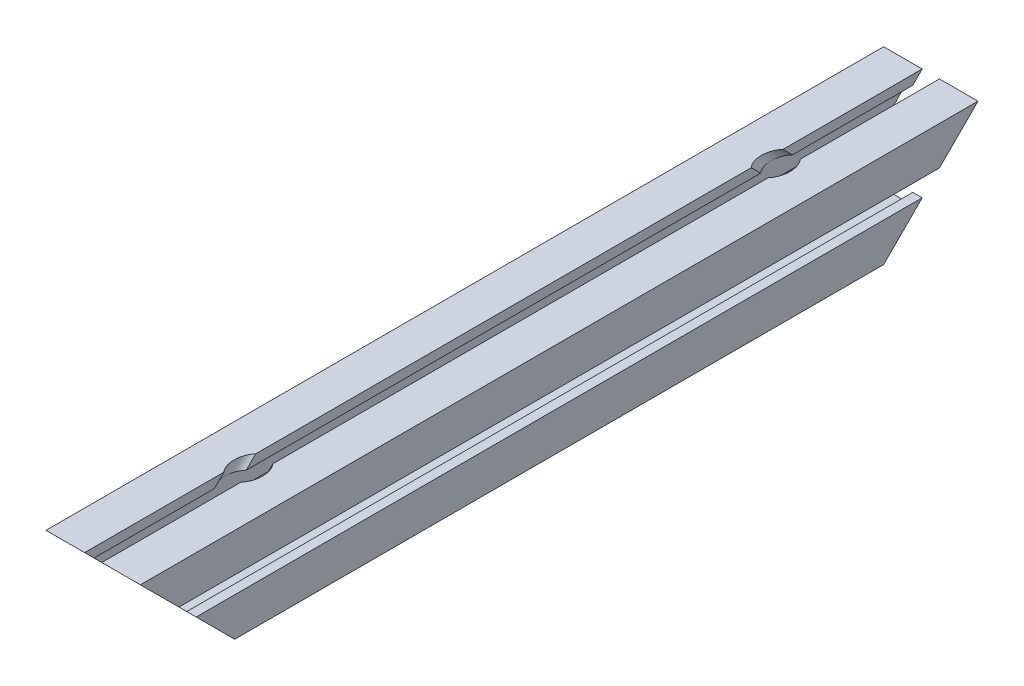
SolidWorks part; units mm, degrees
material "6061 Alloy"
ref_plane "Front Plane" through (0, 0, 0) normal (0, 0, 1) x (1, 0, 0)
ref_plane "Top Plane" through (0, 0, 0) normal (0, 1, 0) x (1, 0, 0)
ref_plane "Right Plane" through (0, 0, 0) normal (1, 0, 0) x (0, 0, -1)
sketch "Sketch1" plane through (0, 0, 0) normal (0, 0, 1) x (1, 0, 0)
  line L88 (-18, -4.1) -> (-22.5, -4.1)
  line L89 (-22.5, -4.1) -> (-22.5, -22.5)
  line L90 (-22.5, -22.5) -> (-4.1, -22.5)
  line L91 (-4.1, -22.5) -> (-4.1, -18)
  line L92 (-4.1, -18) -> (-6.8, -18)
  line L93 (-6.8, -18) -> (-6.8, -9.5)
  line L94 (-6.8, -9.5) -> (-4.5, -7.2)
  line L95 (-4.5, -7.2) -> (4.5, -7.2)
  line L96 (4.5, -7.2) -> (6.8, -9.5)
  line L97 (6.8, -9.5) -> (6.8, -18)
  line L98 (6.8, -18) -> (4.1, -18)
  line L99 (4.1, -18) -> (4.1, -22.5)
  line L100 (4.1, -22.5) -> (22.5, -22.5)
  line L101 (22.5, -22.5) -> (22.5, -4.1)
  line L102 (22.5, -4.1) -> (18, -4.1)
  line L103 (18, -4.1) -> (18, -6.8)
  line L104 (18, -6.8) -> (9.5, -6.8)
  line L105 (9.5, -6.8) -> (7.2, -4.5)
  line L106 (7.2, -4.5) -> (7.2, 4.5)
  line L107 (7.2, 4.5) -> (9.5, 6.8)
  line L108 (9.5, 6.8) -> (18, 6.8)
  line L109 (18, 6.8) -> (18, 4.1)
  line L110 (18, 4.1) -> (22.5, 4.1)
  line L111 (22.5, 4.1) -> (22.5, 22.5)
  line L112 (22.5, 22.5) -> (4.1, 22.5)
  line L113 (4.1, 22.5) -> (4.1, 18)
  line L114 (4.1, 18) -> (6.8, 18)
  line L115 (6.8, 18) -> (6.8, 9.5)
  line L116 (6.8, 9.5) -> (4.5, 7.2)
  line L117 (4.5, 7.2) -> (-4.5, 7.2)
  line L118 (-4.5, 7.2) -> (-6.8, 9.5)
  line L119 (-6.8, 9.5) -> (-6.8, 18)
  line L120 (-6.8, 18) -> (-4.1, 18)
  line L121 (-4.1, 18) -> (-4.1, 22.5)
  line L122 (-4.1, 22.5) -> (-22.5, 22.5)
  line L123 (-22.5, 22.5) -> (-22.5, 4.1)
  line L124 (-22.5, 4.1) -> (-18, 4.1)
  line L125 (-18, 4.1) -> (-18, 6.8)
  line L126 (-18, 6.8) -> (-9.5, 6.8)
  line L127 (-9.5, 6.8) -> (-7.2, 4.5)
  line L128 (-7.2, 4.5) -> (-7.2, -4.5)
  line L129 (-7.2, -4.5) -> (-9.5, -6.8)
  line L130 (-9.5, -6.8) -> (-18, -6.8)
  line L131 (-18, -6.8) -> (-18, -4.1)
  circle A5 centre (14.65, -14.65) radius 6
  circle A6 centre (-14.65, -14.65) radius 6
  circle A7 centre (0, 0) radius 3.75
  circle A8 centre (14.65, 14.65) radius 6
  circle A9 centre (-14.65, 14.65) radius 6
extrude "Extrude1" add sketch "Sketch1" along normal blind 199.7577 and the other way blind 199.7577
sketch "Sketch2" plane through (22.5, 0, 0) normal (1, 0, 0) x (0, 0, -1)
  line L0 (-199.7577, 4.1) -> (-199.7577, 22.5) construction
  line L1 (-199.7577, 4.1) -> (-199.7577, 22.5)
  line L2 (199.7577, -22.5) -> (-199.7577, -22.5) construction
  line L3 (199.7577, -22.5) -> (-199.7577, -22.5)
  line L4 (-199.7577, 22.5) -> (-154.7577, -22.5)
  line L5 (-154.7577, -22.5) -> (-199.7577, -22.5)
  line L6 (-199.7577, -22.5) -> (-199.7577, 22.5)
  line L7 (199.7577, 22.5) -> (199.7577, -22.5)
  line L8 (199.7577, -22.5) -> (154.7577, -22.5)
  line L9 (154.7577, -22.5) -> (199.7577, 22.5)
  line M2 (-199.7577, 22.5) -> (-199.7577, 4.1)
  line M3 (-199.7577, 4.1) -> (199.7577, 4.1)
  line M4 (199.7577, 4.1) -> (199.7577, 22.5)
  dimension "D1" = 45
  dimension "D2" = 45
extrude "Extrude2" cut sketch "Sketch2" against normal through all contours L6 L3 L4 M3 | L4 M2 M3 | L9 L3 L7 M3 | L9 M3 M4
ref_plane "Plane1" through (0, -73.3624, 73.3624) normal (0, -0.7071, 0.7071) x (1, 0, 0)
sketch "Sketch3" plane through (0, -88.6288, 88.6288) normal (0, -0.7071, 0.7071) x (1, 0, 0)
  line L0 (22.5, 157.1599) -> (22.5, 131.1384) construction
  line L1 (22.5, 157.1599) -> (4.1, 157.1599) construction
  circle A0 centre (0, 104.8359) radius 4.25
  dimension "D3" = 8.5
  dimension "D1" = 22.5
  dimension "D2" = 52.324
extrude "Extrude3" cut sketch "Sketch3" against normal through all
sketch "Sketch4" plane through (0, -73.3624, 73.3624) normal (0, -0.7071, 0.7071) x (1, 0, 0)
  circle A0 centre (0, 104.8359) radius 4.25 construction
  circle A1 centre (0, 104.8359) radius 4.25
  circle A2 centre (0, 104.8359) radius 6.75
  dimension "D1" = 13.5
extrude "Extrude4" cut sketch "Sketch4" against normal through all
mirror "Mirror1" about plane through (0, 0, 0) normal (0, 0, 1) of "Extrude3", "Extrude4"
